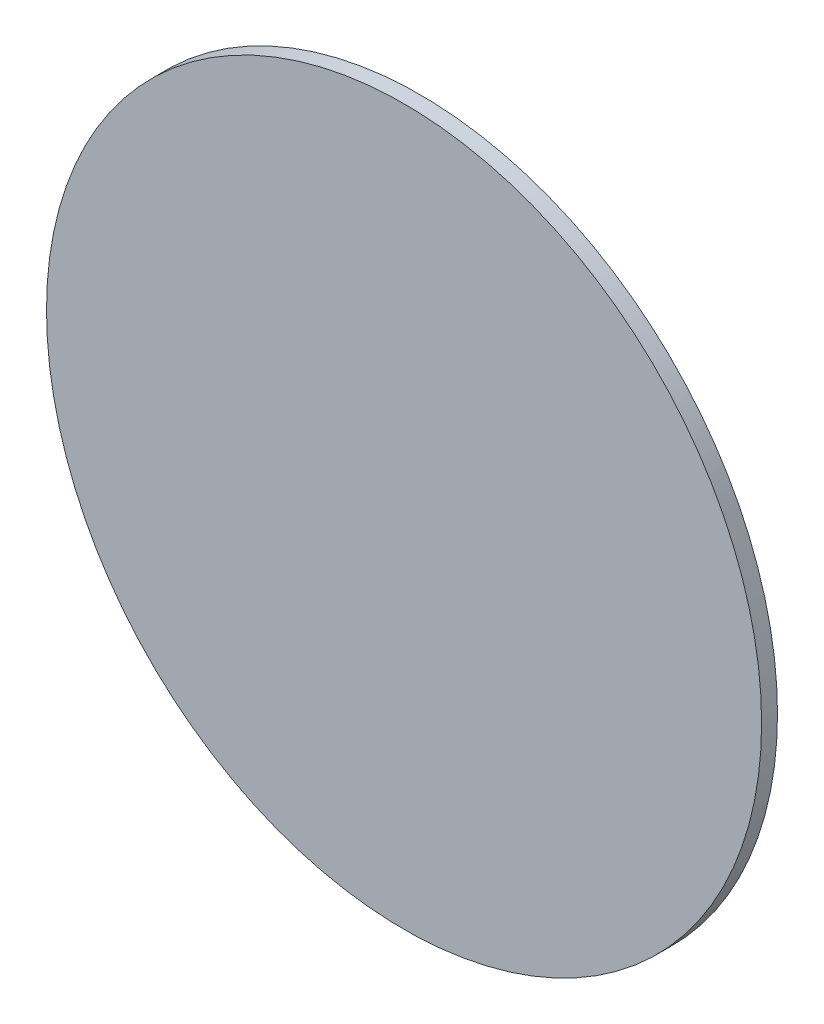
SolidWorks part; units mm, degrees
ref_plane "Front Plane" through (0, 0, 0) normal (0, 0, 1) x (1, 0, 0)
ref_plane "Top Plane" through (0, 0, 0) normal (0, 1, 0) x (1, 0, 0)
ref_plane "Right Plane" through (0, 0, 0) normal (1, 0, 0) x (0, 0, -1)
sketch "Sketch2" plane through (0, 0, 0) normal (0, 0, 1) x (1, 0, 0)
  circle A0 centre (0, 0) radius 45
  dimension "D1" = 90
extrude "Boss-Extrude1" add sketch "Sketch2" along normal blind 2
